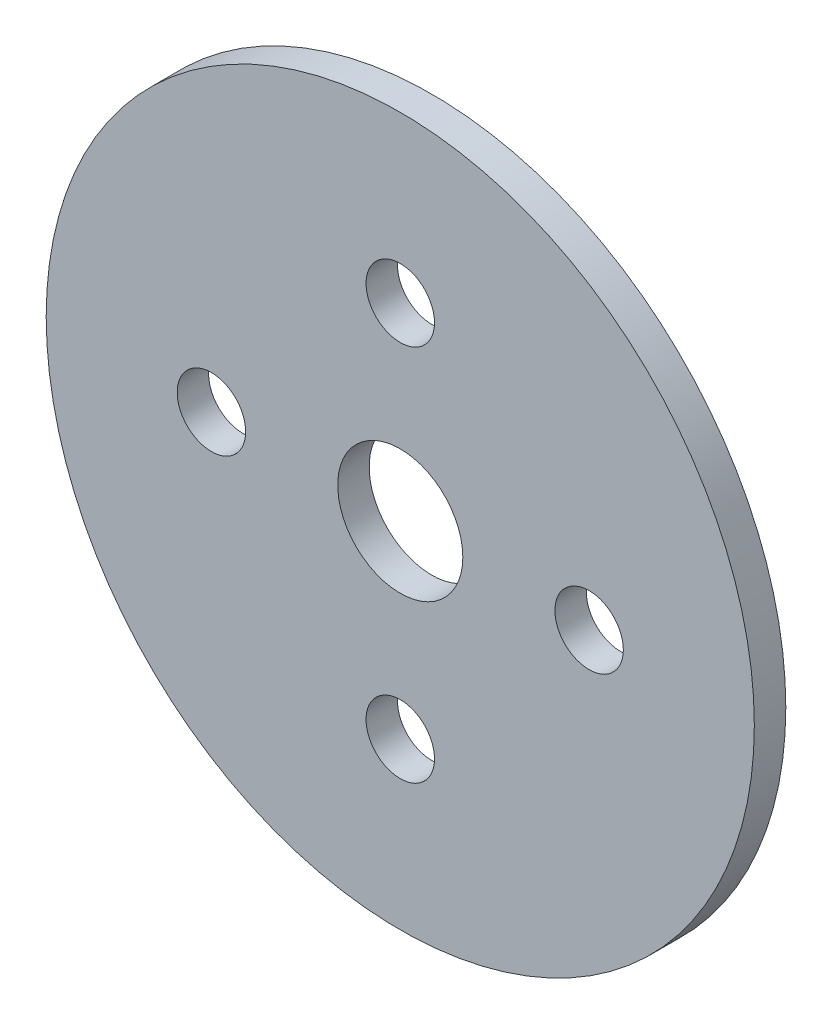
SolidWorks part; units mm, degrees
ref_plane "Front Plane" through (0, 0, 0) normal (0, 0, 1) x (1, 0, 0)
ref_plane "Top Plane" through (0, 0, 0) normal (0, 1, 0) x (1, 0, 0)
ref_plane "Right Plane" through (0, 0, 0) normal (1, 0, 0) x (0, 0, -1)
sketch "Sketch1" plane through (0, 0, 0) normal (0, 0, 1) x (1, 0, 0)
  circle A0 centre (0, 0) radius 22.5
  circle A2 centre (12, 0) radius 2.175
  circle A3 centre (0, 12) radius 2.175
  circle A4 centre (-12, 0) radius 2.175
  circle A5 centre (0, -12) radius 2.175
  circle A6 centre (0, 0) radius 3.975
  dimension "D1" = 4.35
  dimension "D2" = 4.35
  dimension "D3" = 4.35
  dimension "D4" = 4.35
  dimension "D5" = 7.95
  dimension "D6" = 45
extrude "Boss-Extrude1" add sketch "Sketch1" along normal blind 2
